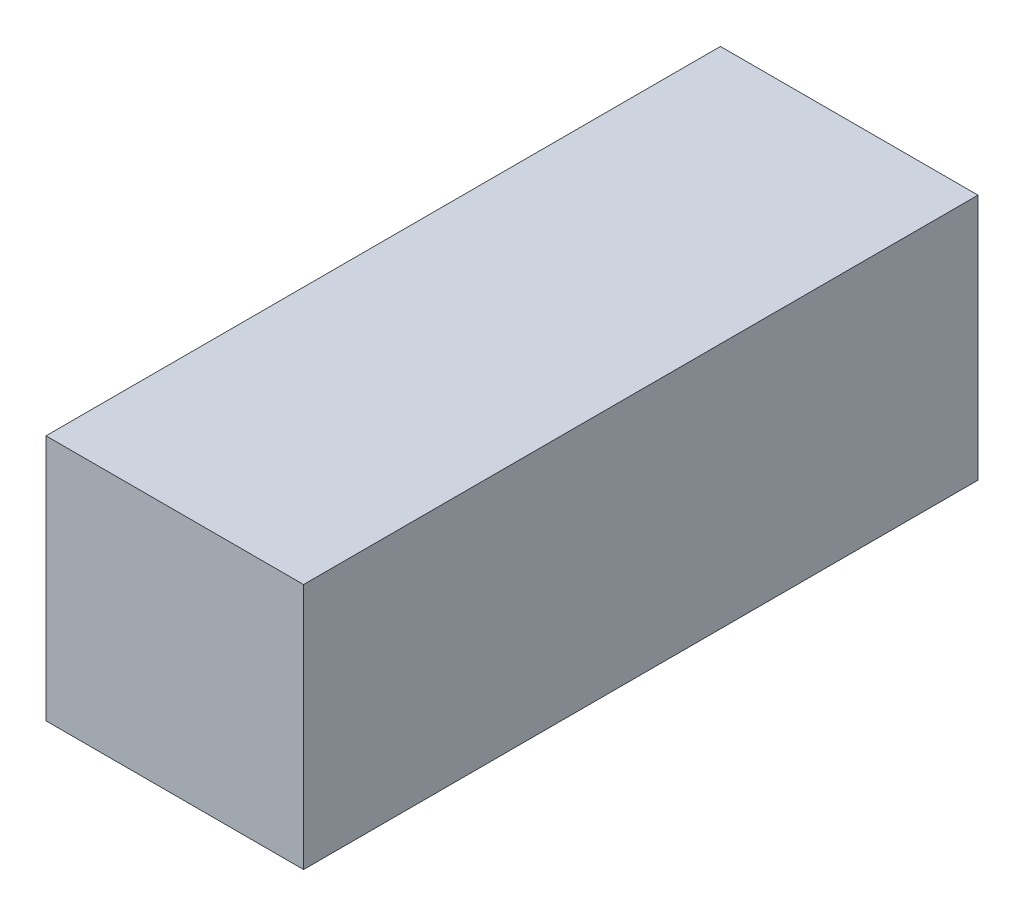
SolidWorks part; units mm, degrees
ref_plane "Front Plane" through (0, 0, 0) normal (0, 0, 1) x (1, 0, 0)
ref_plane "Top Plane" through (0, 0, 0) normal (0, 1, 0) x (1, 0, 0)
ref_plane "Right Plane" through (0, 0, 0) normal (1, 0, 0) x (0, 0, -1)
sketch "Sketch1" plane through (0, 0, 0) normal (0, 0, 1) x (1, 0, 0)
  line L1 (-1.2126, -1.1621) -> (1.2126, -1.1621)
  line L2 (-1.2126, -1.1621) -> (-1.2126, 1.1621)
  line L3 (-1.2126, 1.1621) -> (1.2126, 1.1621)
  line L4 (1.2126, -1.1621) -> (1.2126, 1.1621)
  line L5 (-1.2126, -1.1621) -> (1.2126, 1.1621) construction
  line L6 (-1.2126, 1.1621) -> (1.2126, -1.1621) construction
  point P0 (0, 0)
extrude "Boss-Extrude1" add sketch "Sketch1" along normal blind 6.35
